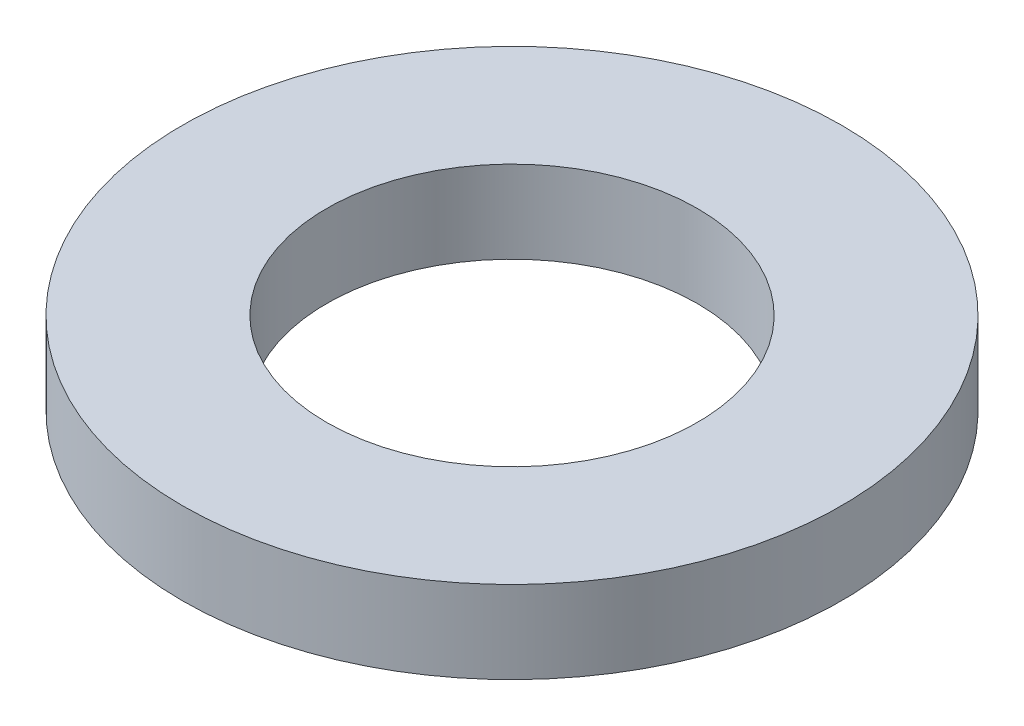
SolidWorks part; units mm, degrees
ref_plane "Front Plane" through (0, 0, 0) normal (0, 0, 1) x (1, 0, 0)
ref_plane "Top Plane" through (0, 0, 0) normal (0, 1, 0) x (1, 0, 0)
ref_plane "Right Plane" through (0, 0, 0) normal (1, 0, 0) x (0, 0, -1)
sketch "Sketch1" plane through (0, 0, 0) normal (0, 1, 0) x (1, 0, 0)
  circle A0 centre (0, 0) radius 10.16
  dimension "OD" = 20.32
extrude "Boss-Extrude1" add sketch "Sketch1" along normal blind 2.54
sketch "Sketch5" plane through (0, 2.54, 0) normal (0, 1, 0) x (-1, 0, 0)
  circle A0 centre (0, 0) radius 5.715
  dimension "ID" = 11.43
extrude "Cut-Extrude1" cut sketch "Sketch5" against normal through all
